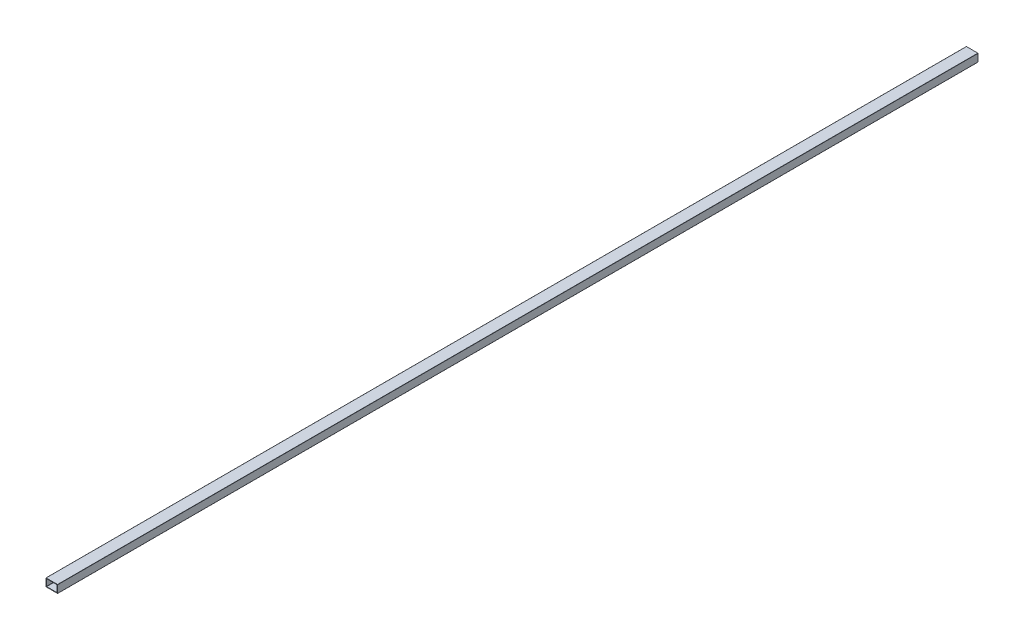
SolidWorks part; units mm, degrees
material "AISI 1035 Acero (SS)"
ref_plane "Alzado" through (0, 0, 0) normal (0, 0, 1) x (1, 0, 0)
ref_plane "Planta" through (0, 0, 0) normal (0, 1, 0) x (1, 0, 0)
ref_plane "Vista lateral" through (0, 0, 0) normal (1, 0, 0) x (0, 0, -1)
sketch "Croquis1" plane through (0, 0, 0) normal (0, 0, 1) x (1, 0, 0)
  line L0 (-35.06, -22.36) -> (-35.06, 22.36)
  line L1 (-38.1, -25.4) -> (38.1, -25.4)
  line L2 (-38.1, -25.4) -> (-38.1, 25.4)
  line L3 (-38.1, 25.4) -> (38.1, 25.4)
  line L4 (38.1, -25.4) -> (38.1, 25.4)
  line L5 (-38.1, -25.4) -> (38.1, 25.4) construction
  line L6 (-38.1, 25.4) -> (38.1, -25.4) construction
  line L7 (-35.06, 22.36) -> (35.06, 22.36)
  line L8 (35.06, -22.36) -> (35.06, 22.36)
  line L9 (-35.06, -22.36) -> (35.06, -22.36)
  point P0 (0, 0)
  dimension "D1" = 50.8
  dimension "D2" = 76.2
  dimension "D3" = 3.04
extrude "Saliente-Extruir1" add sketch "Croquis1" against normal blind 6000
fillet "Redondeo1" radius 1 8 edges at (-35.06, 22.36, -3000) (35.06, 22.36, -3000) (35.06, -22.36, -3000) (-38.1, -25.4, -3000) (-38.1, 25.4, -3000) (-35.06, -22.36, -3000) (38.1, -25.4, -3000) (38.1, 25.4, -3000)
